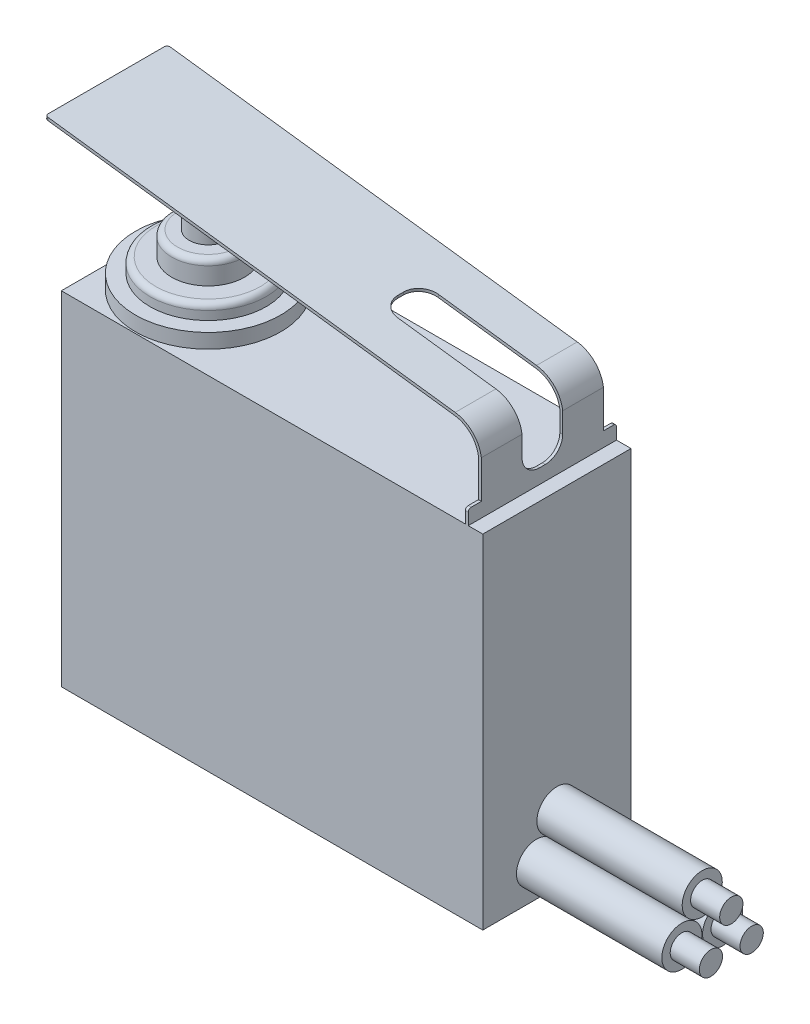
SolidWorks part; units mm, degrees
ref_plane "Płaszczyzna przednia" through (0, 0, 0) normal (0, 0, 1) x (1, 0, 0)
ref_plane "Płaszczyzna górna" through (0, 0, 0) normal (0, 1, 0) x (1, 0, 0)
ref_plane "Płaszczyzna prawa" through (0, 0, 0) normal (1, 0, 0) x (0, 0, -1)
sketch "Szkic2" plane through (0, 0, 0) normal (0, 1, 0) x (1, 0, 0)
  line L1 (7.25, -2.55) -> (-7.25, -2.55)
  line L2 (7.25, -2.55) -> (7.25, 2.55)
  line L3 (7.25, 2.55) -> (-7.25, 2.55)
  line L4 (-7.25, -2.55) -> (-7.25, 2.55)
  line L5 (7.25, -2.55) -> (-7.25, 2.55) construction
  line L6 (7.25, 2.55) -> (-7.25, -2.55) construction
  point P0 (0, 0)
  dimension "D1" = 14.5
  dimension "D2" = 5.1
extrude "Dodanie-wyciągnięcie1" add sketch "Szkic2" along normal blind 11.8
sketch "Szkic3" plane through (0, 11.8, 0) normal (0, 1, 0) x (1, 0, 0)
  line L0 (-7.25, 0) -> (-4.75, 0) construction
  line L1 (-7.25, 2.55) -> (-7.25, -2.55) construction
  circle A0 centre (-4.75, 0) radius 2.5
  circle A1 centre (-4.75, 0) radius 2
  dimension "D1" = 0.5
extrude "Dodanie-wyciągnięcie2" add sketch "Szkic3" along normal blind 0.5
sketch "Szkic4" plane through (0, 11.8, 0) normal (0, 1, 0) x (1, 0, 0)
  circle A1 centre (-4.75, 0) radius 2
  circle A2 centre (-4.75, 0) radius 2
  dimension "D1" = 0
extrude "Dodanie-wyciągnięcie3" add sketch "Szkic4" along normal blind 1
sketch "Szkic5" plane through (0, 12.8, 0) normal (0, 1, 0) x (1, 0, 0)
  circle A0 centre (-4.75, 0) radius 1.25
extrude "Dodanie-wyciągnięcie4" add sketch "Szkic5" along normal blind 0.8
sketch "Szkic6" plane through (0, 13.6, 0) normal (0, 1, 0) x (1, 0, 0)
  circle A0 centre (-4.75, 0) radius 0.65
extrude "Dodanie-wyciągnięcie5" add sketch "Szkic6" along normal blind 1
fillet "Zaokrąglenie1" radius 0.2 2 edges at (-4.75, 13.6, 1.25) (-4.75, 12.8, 2)
sketch "Szkic10" plane through (0, 0, 2.55) normal (0, 0, 1) x (1, 0, 0)
  line L0 (6.75, 11.8) -> (6.75, 13.6)
  line L1 (6.75, 13.6) -> (5.85, 13.6) construction
  line L2 (5.85, 13.6) -> (5.85, 14.5) construction
  line L3 (5.85, 14.5) -> (-8.25, 16.3)
  line L4 (-7.25, 11.8) -> (-8.25, 11.8) construction
  line L5 (-8.25, 11.8) -> (-8.25, 16.3) construction
  line L6 (-8.25, 16.3) -> (-8.2627, 16.2008)
  line L7 (-8.2627, 16.2008) -> (5.8373, 14.4008)
  line L8 (5.85, 14.5) -> (5.8373, 14.4008) construction
  line L9 (6.65, 11.8) -> (6.65, 13.6)
  line L10 (6.65, 13.6) -> (6.75, 13.6) construction
  line L11 (-7.25, 11.8) -> (7.25, 11.8) construction
  line L16 (-7.25, 0) -> (7.25, 0)
  line L17 (7.25, 0) -> (7.25, 11.8)
  line L18 (7.25, 11.8) -> (-7.25, 11.8)
  line L19 (-7.25, 11.8) -> (-7.25, 0)
  line L22 (6.75, 11.8) -> (6.65, 11.8)
  arc A0 (5.8373, 14.4008) -> (6.65, 13.6) centre (5.7181, 13.4671) cw
  arc A1 (5.85, 14.5) -> (6.75, 13.6) centre (5.7183, 13.4683) cw
  dimension "D1" = 1.8
  dimension "D2" = 0.9
  dimension "D3" = 0.9
  dimension "D4" = 1
  dimension "D5" = 4.5
  dimension "D6" = 90
  dimension "D7" = 0.1
  dimension "D8" = 90
  dimension "D9" = 0.1
  dimension "D10" = 0.1
  dimension "D11" = 0.5
  dimension "D12" = 0
extrude "Dodanie-wyciągnięcie7" add sketch "Szkic10" against normal up to surface (5.1 mm away) up to face at (0, 5.9, -2.55)
sketch "Szkic11" plane through (6.75, 0, 0) normal (1, 0, 0) x (0, 0, -1)
  line L0 (-2.55, 12.3) -> (-2.1, 12.3)
  line L1 (-2.55, 11.8) -> (-2.55, 13.6) construction
  line L2 (-2.1, 12.3) -> (-2.1, 17.7015)
  line L3 (-2.1, 17.7015) -> (-2.55, 17.7015)
  line L4 (-2.55, 17.7015) -> (-2.55, 12.3)
  line L5 (0, 11.8) -> (0, 18.3839) construction
  line L6 (2.55, 11.8) -> (-2.55, 11.8) construction
  line L7 (2.55, 17.7015) -> (2.55, 12.3)
  line L8 (2.1, 17.7015) -> (2.55, 17.7015)
  line L9 (2.1, 12.3) -> (2.1, 17.7015)
  line L10 (2.55, 12.3) -> (2.1, 12.3)
  line L11 (-2.55, 11.8) -> (2.55, 11.8) construction
  dimension "D1" = 4.2
  dimension "D2" = 0.5
extrude "Wytnij-wyciągnięcie2" cut sketch "Szkic11" against normal through all
sketch "Szkic12" plane through (1.9152, 15.0023, 0) normal (0.1266, 0.9919, 0) x (0.9919, -0.1266, 0)
  line L0 (3.9667, 0) -> (-0.0333, 0) construction
  line L1 (3.9667, 2.1) -> (3.9667, -2.1) construction
  line L2 (-0.0333, 0.1) -> (-0.0333, -0.1)
  line L3 (0.5667, -0.7) -> (3.9667, -0.7)
  line L4 (3.9667, -0.7) -> (3.9667, 0.7) construction
  line L5 (0.5667, 0.7) -> (3.9667, 0.7)
  line L6 (3.9667, -0.7) -> (8.347, -0.7)
  line L7 (8.347, -0.7) -> (8.347, 0.7)
  line L8 (8.347, 0.7) -> (3.9667, 0.7)
  arc A0 (-0.0333, -0.1) -> (0.5667, -0.7) centre (0.5667, -0.1) ccw
  arc A1 (-0.0333, 0.1) -> (0.5667, 0.7) centre (0.5667, 0.1) cw
  dimension "D1" = 0.6
  dimension "D2" = 0.2
  dimension "D3" = 4
extrude "Wytnij-wyciągnięcie3" cut sketch "Szkic12" against normal up to vertex (0.7788 mm away)
sketch "Szkic13" plane through (6.75, 0, 0) normal (1, 0, 0) x (0, 0, -1)
  line L0 (0, 11.8) -> (0, 12.3) construction
  line L1 (2.55, 11.8) -> (-2.55, 11.8) construction
  line L2 (0.1, 12.3) -> (-0.1, 12.3)
  line L3 (-0.7, 12.9) -> (-0.7, 14.0547)
  line L4 (0.7, 12.9) -> (0.7, 14.0547)
  line L5 (-0.7, 14.0547) -> (0.7, 14.0547)
  arc A0 (-0.1, 12.3) -> (-0.7, 12.9) centre (-0.1, 12.9) cw
  arc A1 (0.1, 12.3) -> (0.7, 12.9) centre (0.1, 12.9) ccw
  dimension "D1" = 0.6
  dimension "D2" = 0.2
extrude "Wytnij-wyciągnięcie4" cut sketch "Szkic13" against normal blind 5
fillet "Zaokrąglenie2" radius 0.1 1 edges at (-4.75, 14.6, 0.65)
sketch "Szkic14" plane through (7.25, 0, 0) normal (1, 0, 0) x (0, 0, -1)
  line L0 (0, 0) -> (0, 3) construction
  line L1 (-2.55, 0) -> (2.55, 0) construction
  circle A0 centre (0, 2.31) radius 0.69
  circle A1 centre (0.7015, 1.095) radius 0.69
  circle A2 centre (-0.7015, 1.095) radius 0.69
  point P8 (0, 1.5)
  point P9 (0, 1.5)
  point P15 (0, 1.5)
  dimension "D2" = 3
  dimension "D3" = 1.38
  dimension "D1" = 3
extrude "Dodanie-wyciągnięcie8" add sketch "Szkic14" along normal blind 5
sketch "Szkic15" plane through (12.25, 0, 0) normal (1, 0, 0) x (0, 0, -1)
  circle A0 centre (0, 2.31) radius 0.4
  circle A1 centre (0.7015, 1.095) radius 0.4
  circle A2 centre (-0.7015, 1.095) radius 0.4
  dimension "D1" = 0.8
extrude "Dodanie-wyciągnięcie9" add sketch "Szkic15" along normal blind 1
fillet "Zaokrąglenie3" radius 0.1 4 edges at (6.7, 12.3, -2.55) (6.7, 12.3, 2.55) (-8.2563, 16.2504, -2.1) (-8.2563, 16.2504, 2.1)
